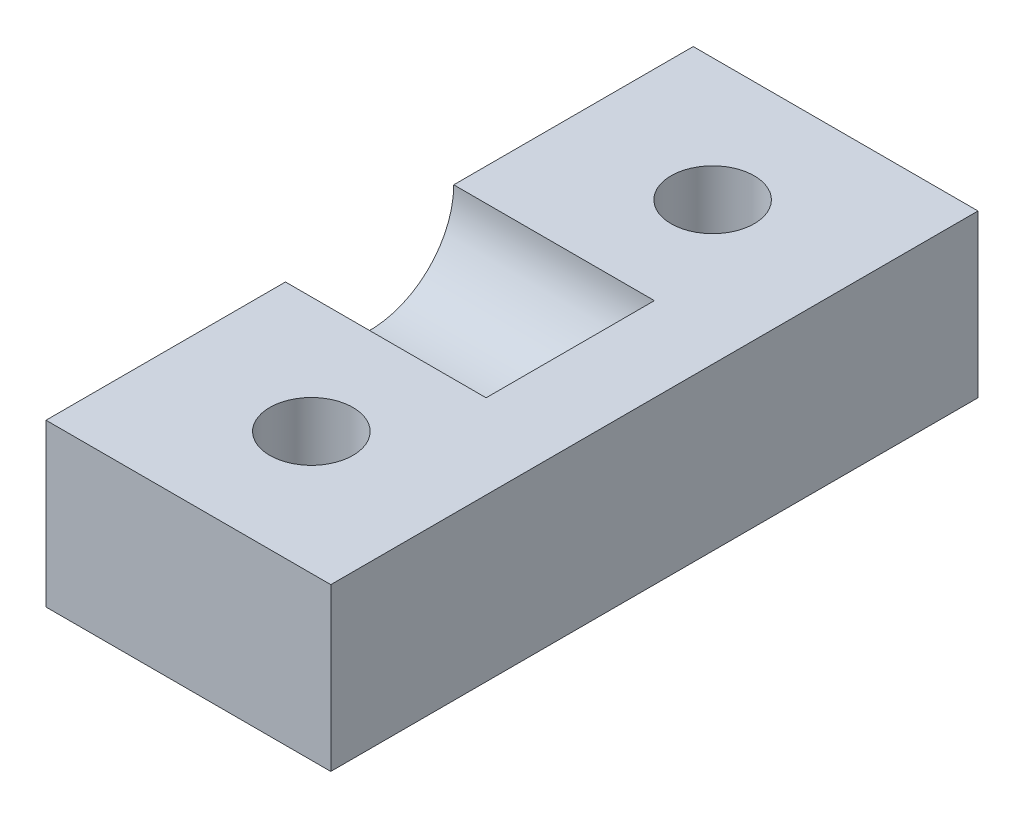
SolidWorks part; units mm, degrees
ref_plane "Front Plane" through (0, 0, 0) normal (0, 0, 1) x (1, 0, 0)
ref_plane "Top Plane" through (0, 0, 0) normal (0, 1, 0) x (1, 0, 0)
ref_plane "Right Plane" through (0, 0, 0) normal (1, 0, 0) x (0, 0, -1)
sketch "Sketch1" plane through (0, 0, 0) normal (0, 1, 0) x (1, 0, 0)
  line L1 (-5.588, -12.7) -> (5.588, -12.7)
  line L2 (-5.588, -12.7) -> (-5.588, 12.7)
  line L3 (-5.588, 12.7) -> (5.588, 12.7)
  line L4 (5.588, -12.7) -> (5.588, 12.7)
  line L5 (-5.588, -12.7) -> (5.588, 12.7) construction
  line L6 (-5.588, 12.7) -> (5.588, -12.7) construction
  point P0 (0, 0)
  dimension "D1" = 11.176
  dimension "D2" = 25.4
extrude "Boss-Extrude1" add sketch "Sketch1" against normal blind 6.35
sketch "Sketch2" plane through (-5.588, 0, 0) normal (-1, 0, 0) x (0, 0, 1)
  circle A0 centre (0, 0) radius 3.302
  dimension "D1" = 6.604
extrude "Cut-Extrude1" cut sketch "Sketch2" against normal blind 7.874
sketch "Sketch3" plane through (0, 0, 0) normal (0, 1, 0) x (1, 0, 0)
  line L0 (5.588, -12.7) -> (5.588, 12.7) construction
  line L1 (5.588, 12.7) -> (-5.588, 12.7) construction
  line L2 (5.588, -12.7) -> (5.588, 12.7) construction
  line L3 (-5.588, -12.7) -> (5.588, -12.7) construction
  circle A0 centre (0, 7.874) radius 1.6319
  circle A1 centre (0, -7.874) radius 1.6319
  dimension "D1" = 3.2639
  dimension "D2" = 3.2639
  dimension "D3" = 5.588
  dimension "D4" = 4.826
  dimension "D5" = 5.588
  dimension "D6" = 4.826
extrude "Cut-Extrude2" cut sketch "Sketch3" against normal up to next
